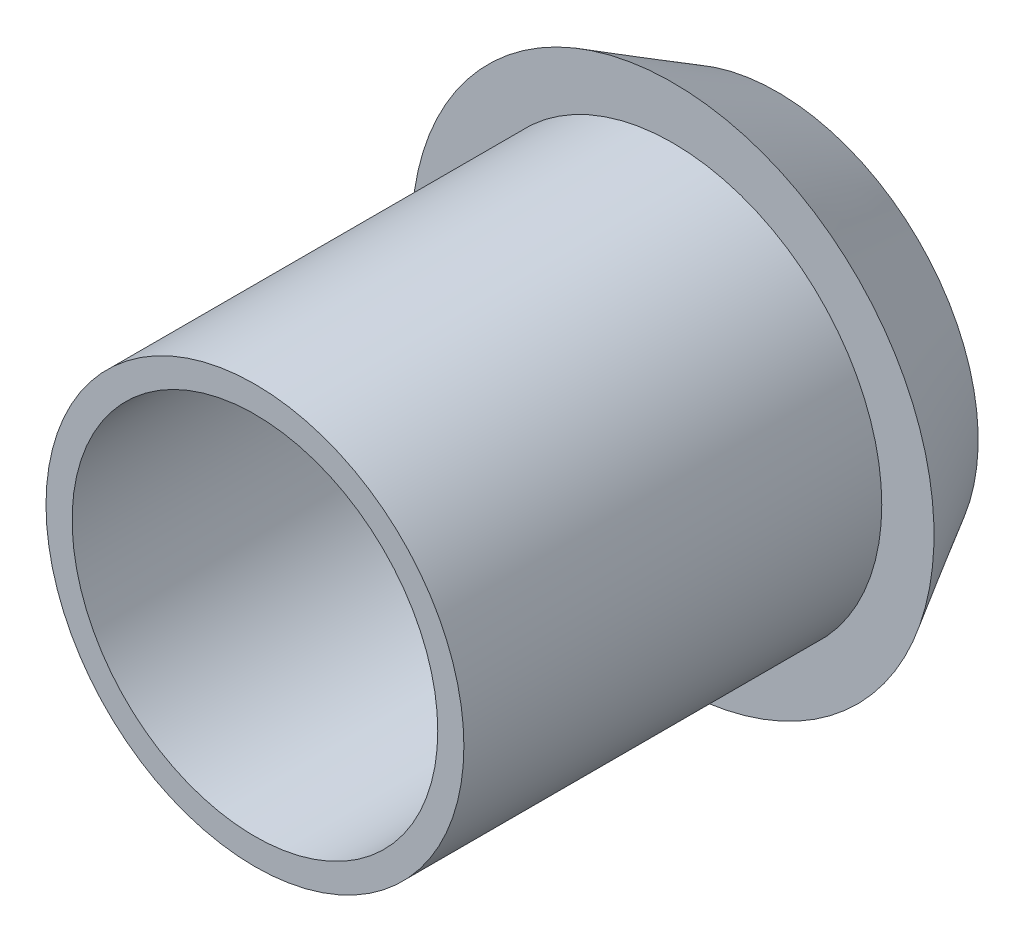
SolidWorks part; units mm, degrees
ref_plane "Front Plane" through (0, 0, 0) normal (0, 0, 1) x (1, 0, 0)
ref_plane "Top Plane" through (0, 0, 0) normal (0, 1, 0) x (1, 0, 0)
ref_plane "Right Plane" through (0, 0, 0) normal (1, 0, 0) x (0, 0, -1)
sketch "Sketch2" plane through (0, 0, 0) normal (0, 0, 1) x (1, 0, 0)
  circle A0 centre (0, 0) radius 4
  circle A1 centre (0, 0) radius 3.5
  dimension "D1" = 8
  dimension "D2" = 7
extrude "Boss-Extrude1" add sketch "Sketch2" along normal blind 8
sketch "Sketch3" plane through (0, 0, 0) normal (0, 0, -1) x (-1, 0, 0)
  circle A0 centre (0, 0) radius 5
  dimension "D1" = 10
extrude "Boss-Extrude2" add sketch "Sketch3" along normal blind 2 draft 30
